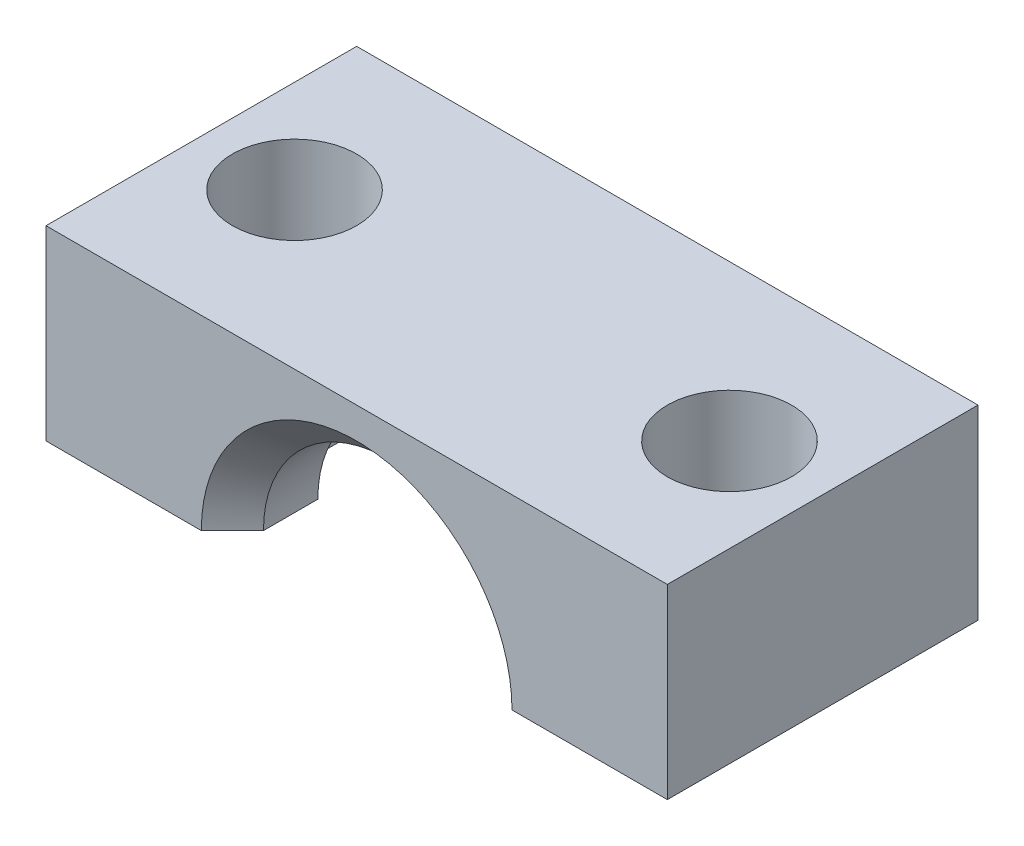
SolidWorks part; units mm, degrees
ref_plane "Спереди" through (0, 0, 0) normal (0, 0, 1) x (1, 0, 0)
ref_plane "Сверху" through (0, 0, 0) normal (0, 1, 0) x (1, 0, 0)
ref_plane "Справа" through (0, 0, 0) normal (1, 0, 0) x (0, 0, -1)
sketch "Эскиз2" plane through (0, 0, 0) normal (0, 0, 1) x (1, 0, 0)
  line L1 (-10, 0) -> (10, 0)
  line L2 (-10, 0) -> (-10, 6)
  line L3 (-10, 6) -> (10, 6)
  line L4 (10, 0) -> (10, 6)
  point P4 (0, 0)
  dimension "D1" = 20
  dimension "D2" = 6
extrude "тело" add sketch "Эскиз2" along normal mid plane 10
sketch "Эскиз3" plane through (0, 0, 5) normal (0, 0, 1) x (1, 0, 0)
  line L0 (-10, 0) -> (10, 0) construction
  circle A0 centre (0, 0) radius 4
  dimension "D1" = 8
extrude "вырез под гайки" cut sketch "Эскиз3" against normal through all
sketch "Эскиз4" plane through (0, 0, 0) normal (0, 0, 1) x (1, 0, 0)
  circle A0 centre (0, 0) radius 5.25
  dimension "D1" = 10.5
extrude "вырез под подшипник" cut sketch "Эскиз4" against normal mid plane 4.5
sketch "Эскиз5" plane through (0, 6, 0) normal (0, 1, 0) x (1, 0, 0)
  line L0 (-7, 0) -> (7, 0) construction
  circle A0 centre (-7, 0) radius 1.2
  circle A1 centre (7, 0) radius 1.2
  point P4 (0, 0)
  dimension "D1" = 2.4
  dimension "D2" = 14
extrude "крепежные отверстия" cut sketch "Эскиз5" against normal through all
chamfer "Фаска2" distance 1 angle 45 2 edges at (0, 4, -5) (0, 4, 5)
sketch "Эскиз6" plane through (0, 6, 0) normal (0, 1, 0) x (1, 0, 0)
  circle A0 centre (-7, 0) radius 2
  circle A1 centre (7, 0) radius 2
  dimension "D1" = 4
extrude "Углубления под шляпки" cut sketch "Эскиз6" against normal blind 4
